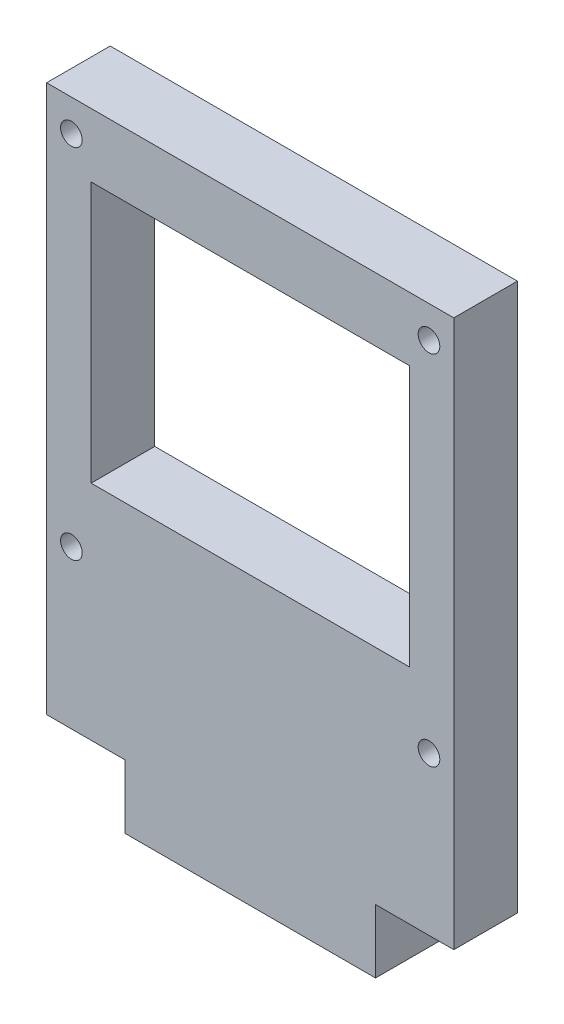
SolidWorks part; units mm, degrees
ref_plane "Front Plane" through (0, 0, 0) normal (0, 0, 1) x (1, 0, 0)
ref_plane "Top Plane" through (0, 0, 0) normal (0, 1, 0) x (1, 0, 0)
ref_plane "Right Plane" through (0, 0, 0) normal (1, 0, 0) x (0, 0, -1)
sketch "Sketch2" plane through (0, 0, 0) normal (0, 1, 0) x (1, 0, 0)
  line L1 (-9.85, 5) -> (9.85, 5)
  line L2 (-9.85, 5) -> (-9.85, 0)
  line L3 (-9.85, 0) -> (9.85, 0)
  line L4 (9.85, 5) -> (9.85, 0)
  point P12 (0, 0)
  dimension "D4" = 5
  dimension "D5" = 19.7
extrude "Boss-Extrude1" add sketch "Sketch2" along normal blind 5
sketch "Sketch4" plane through (0, 0, 0) normal (0, 0, 1) x (1, 0, 0)
  line L0 (-16, 5) -> (16, 5)
  line L2 (-16, 5) -> (-16, 48)
  line L5 (-12.5, 22.5) -> (12.5, 22.5)
  line L9 (-12.5, 22.5) -> (-12.5, 43)
  line L10 (-12.5, 43) -> (0, 43)
  line L12 (-16, 48) -> (0, 48)
  line L13 (0, 5) -> (0, 22.5) construction
  line L14 (16, 48) -> (0, 48)
  line L16 (12.5, 43) -> (0, 43)
  line L17 (12.5, 22.5) -> (12.5, 43)
  line L18 (16, 5) -> (16, 48)
  line L19 (-9.85, 5) -> (9.85, 5) construction
  dimension "D1" = 3.5
  dimension "D2" = 43
  dimension "D3" = 17.5
  dimension "D5" = 5
  dimension "D6" = 16
extrude "Boss-Extrude2" add sketch "Sketch4" against normal up to surface (5 mm away) up to face at (0, 2.5, -5)
sketch "Sketch5" plane through (0, 0, 0) normal (0, 0, 1) x (1, 0, 0)
  line L0 (0, 0) -> (0, 22.5) construction
  line L1 (-9.85, 0) -> (9.85, 0) construction
  line L2 (-12.5, 22.5) -> (12.5, 22.5) construction
  line L3 (-14.05, 44.65) -> (-14.05, 18.25) construction
  line L4 (-12.5, 43) -> (-12.5, 48) construction
  line L7 (16, 48) -> (-16, 48) construction
  circle A0 centre (-14.05, 45.5) radius 0.85
  circle A1 centre (-14.05, 17.4) radius 0.85
  circle A2 centre (14.05, 17.4) radius 0.85
  circle A3 centre (14.05, 45.5) radius 0.85
  point P12 (-12.5, 45.5)
  dimension "D2" = 1.7
  dimension "D1" = 26.4
  dimension "D3" = 14.05
extrude "Cut-Extrude1" cut sketch "Sketch5" against normal up to surface (5 mm away) up to face at (0, 14.5, -5)
equation "\"D3@Sketch5\"=(\"D1@Sketch5\"/2)+(\"D2@Sketch5\"/2)"
